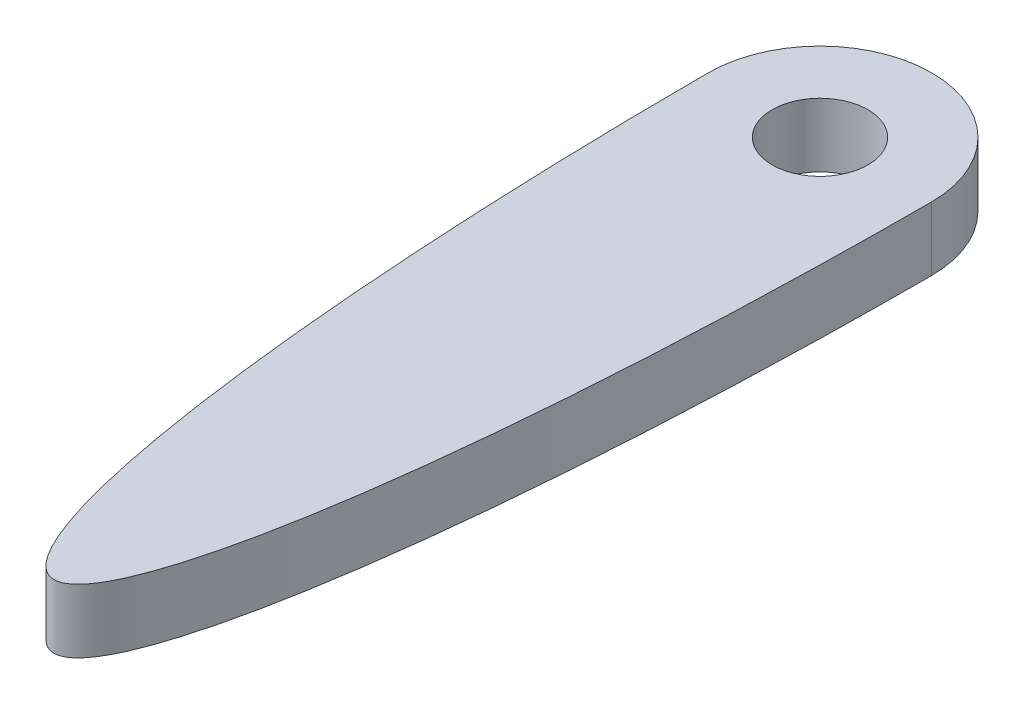
SolidWorks part; units mm, degrees
ref_plane "Front Plane" through (0, 0, 0) normal (0, 0, 1) x (1, 0, 0)
ref_plane "Top Plane" through (0, 0, 0) normal (0, 1, 0) x (1, 0, 0)
ref_plane "Right Plane" through (0, 0, 0) normal (1, 0, 0) x (0, 0, -1)
sketch "Sketch1" plane through (0, 0, 0) normal (0, 1, 0) x (1, 0, 0)
  circle A0 centre (0, 0) radius 2.3813
  circle A1 centre (0, 0) radius 5.5563
  ellipse E0 centre (0, 0) end of major axis (0, 38.1) minor radius 5.5562 (-5.5562, 0) -> (5.5562, 0) ccw
  dimension "D1" = 4.7625
  dimension "D2" = 3.175
extrude "Boss-Extrude1" add sketch "Sketch1" along normal blind 3.175 contours A1 E0 | A1 A0
